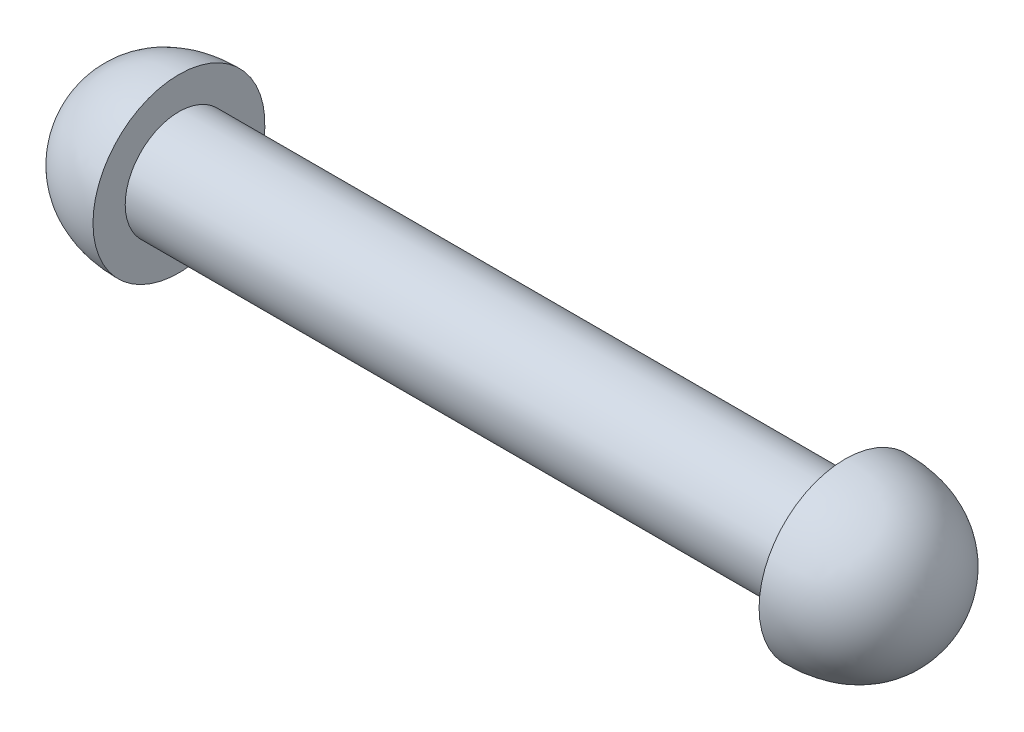
SolidWorks part; units mm, degrees
ref_plane "Front Plane" through (0, 0, 0) normal (0, 0, 1) x (1, 0, 0)
ref_plane "Top Plane" through (0, 0, 0) normal (0, 1, 0) x (1, 0, 0)
ref_plane "Right Plane" through (0, 0, 0) normal (1, 0, 0) x (0, 0, -1)
sketch "Sketch1" plane through (0, 0, 0) normal (1, 0, 0) x (0, 0, -1)
  circle A0 centre (0, 0) radius 25
  dimension "D1" = 50
extrude "Boss-Extrude1" add sketch "Sketch1" along normal blind 155
sketch "Sketch3" plane through (0, 0, 0) normal (0, 0, 1) x (1, 0, 0)
  line L2 (-100.0787, 0) -> (83.5342, 0) construction
  line L3 (0, 0) -> (-45.4584, 0)
  line L4 (0, 40) -> (0, 0)
  spline S0 degree 3 poles (-45.4584, 0) (-45.4584, 20.1838) (-30.9912, 40) (0, 40) knots 0 0 0 0 1 1 1 1
  dimension "D1" = 40
revolve "Revolve1" add sketch "Sketch3" angle 360 about L2
mirror "Mirror1" about plane through (155, 0, 0) normal (1, 0, 0) of "Boss-Extrude1", "Revolve1"
